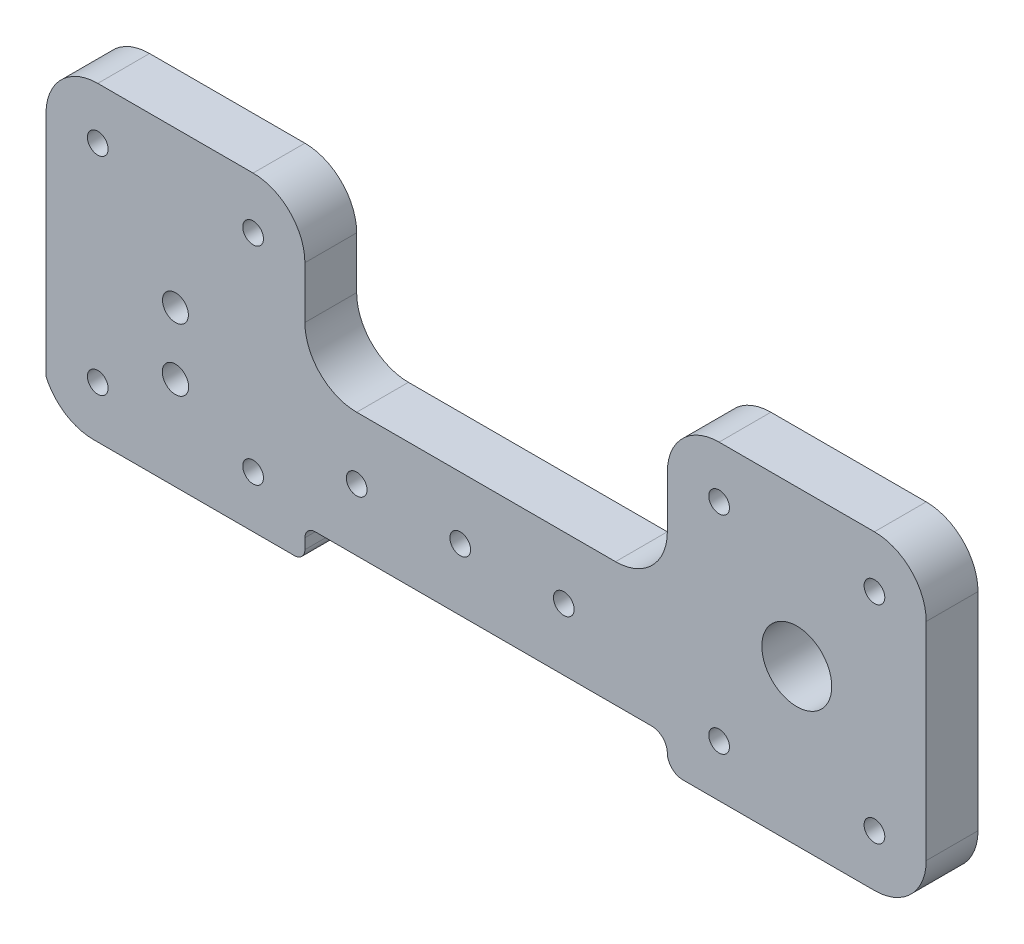
SolidWorks part; units mm, degrees
ref_plane "Front Plane" through (0, 0, 0) normal (0, 0, 1) x (1, 0, 0)
ref_plane "Top Plane" through (0, 0, 0) normal (0, 1, 0) x (1, 0, 0)
ref_plane "Right Plane" through (0, 0, 0) normal (1, 0, 0) x (0, 0, -1)
sketch "Model" plane through (0, 0, 0) normal (0, 0, 1) x (1, 0, 0)
  line L0 (-13.0894, 50) -> (-13.0894, 6)
  line L1 (26.9106, 60) -> (-3.0894, 60)
  line L2 (36.9106, 40) -> (36.9106, 50)
  line L3 (96.9106, 30) -> (46.9106, 30)
  line L4 (106.9106, 50) -> (106.9106, 40)
  line L5 (146.9106, 60) -> (116.9106, 60)
  line L6 (156.9106, 10) -> (156.9106, 50)
  line L7 (109.9106, 0) -> (146.9106, 0)
  line L8 (38.9106, 6) -> (103.9106, 6)
  line L9 (36.9106, 2) -> (36.9106, 4)
  line L10 (-3.9243, 0) -> (34.9106, 0)
  circle A0 centre (26.9106, 50) radius 2
  circle A1 centre (26.9106, 10) radius 2
  circle A2 centre (11.9106, 30) radius 2.5
  circle A3 centre (131.9106, 30) radius 6.75
  circle A4 centre (146.9106, 50) radius 2
  circle A5 centre (86.9106, 18) radius 2
  circle A6 centre (146.9106, 10) radius 2
  circle A7 centre (116.9106, 10) radius 2
  circle A8 centre (46.9106, 18) radius 2
  circle A9 centre (66.9106, 18) radius 2
  circle A10 centre (116.9106, 50) radius 2
  circle A11 centre (11.9106, 18) radius 2.55
  circle A12 centre (-3.0894, 10) radius 2
  circle A13 centre (-3.0894, 50) radius 2
  arc A14 (-3.0894, 60) -> (-13.0894, 50) centre (-3.0894, 50) ccw
  arc A15 (36.9106, 50) -> (26.9106, 60) centre (26.9106, 50) ccw
  arc A16 (36.9106, 40) -> (46.9106, 30) centre (46.9106, 40) ccw
  arc A17 (96.9106, 30) -> (106.9106, 40) centre (96.9106, 40) ccw
  arc A18 (116.9106, 60) -> (106.9106, 50) centre (116.9106, 50) ccw
  arc A19 (156.9106, 50) -> (146.9106, 60) centre (146.9106, 50) ccw
  arc A20 (146.9106, 0) -> (156.9106, 10) centre (146.9106, 10) ccw
  arc A21 (106.9106, 3) -> (109.9106, 0) centre (109.9106, 3) ccw
  arc A22 (106.9106, 3) -> (103.9106, 6) centre (103.9106, 3) ccw
  arc A23 (38.9106, 6) -> (36.9106, 4) centre (38.9106, 4) ccw
  arc A24 (34.9106, 0) -> (36.9106, 2) centre (34.9106, 2) ccw
  arc A25 (-13.0894, 6) -> (-3.9243, 0) centre (-3.9243, 10) ccw
extrude "Boss-Extrude1" add sketch "Model" along normal blind 10
sketch "Sketch2" plane through (0, 0, 10) normal (0, 0, 1) x (1, 0, 0)
  text T0 "Copyright © Adarsh Belavatagi and Manikanta Pujar 2018.\r\nThis documentation describes Open Hardware and is licensed under the CERN OHL v. 1.2.\r\nYou may redistribute and modify this documentation under the terms of the CERN OHL v.1.2.\r\n(http://ohwr.org/cernohl). This documentation is distributed WITHOUT ANY EXPRESS OR\r\nIMPLIED WARRANTY, INCLUDING OF MERCHANTABILITY, SATISFACTORY QUALITY AND FITNESS FOR A PARTICULAR PURPOSE.\r\nPlease see the CERN OHL v.1.2 for applicable conditions\r\n\r\nThe full text of the license is available in LICENSE.txt(https://github.com/AdarshBelavatagi/Maudslay/blob/master/LICENSE.txt)\r\n\r\n"
